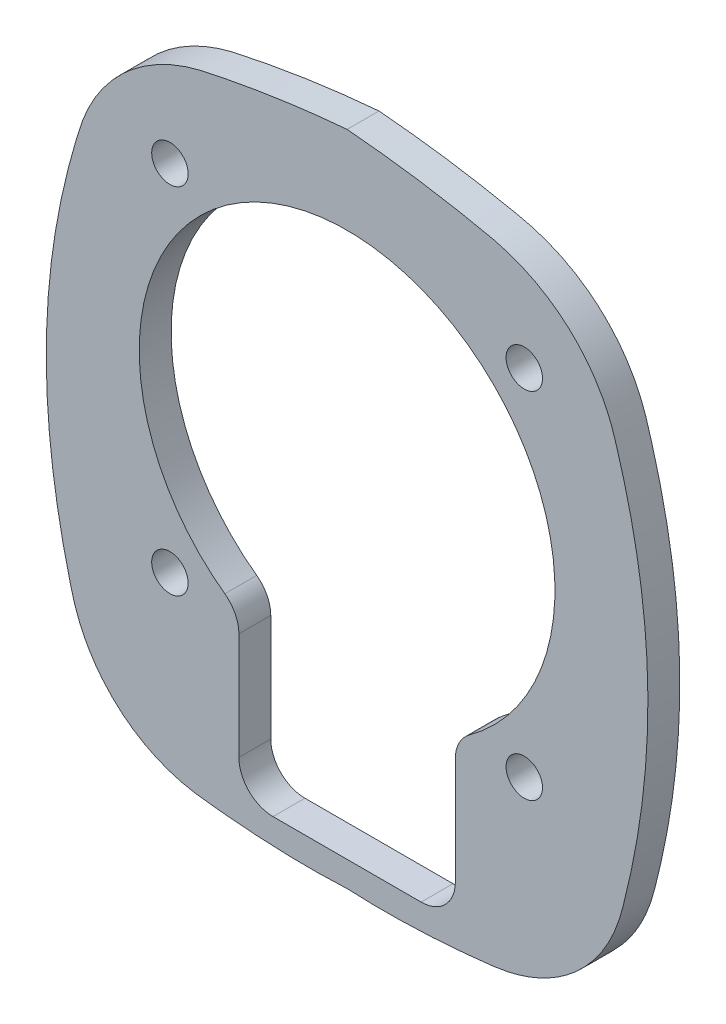
SolidWorks part; units mm, degrees
material "Фанера"
ref_plane "Front Plane" through (0, 0, 0) normal (0, 0, 1) x (1, 0, 0)
ref_plane "Top Plane" through (0, 0, 0) normal (0, 1, 0) x (1, 0, 0)
ref_plane "Right Plane" through (0, 0, 0) normal (1, 0, 0) x (0, 0, -1)
sketch "Эскиз1" plane through (0, 0, 0) normal (0, 0, 1) x (1, 0, 0)
  line L0 (-40.2242, 103.6369) -> (46.2063, 103.6369) construction
  line L1 (0, 130.3745) -> (0, 76.8994) construction
  line L2 (-9.3275, 94.3094) -> (15.3879, 119.0248) construction
  line L3 (0, 85.3869) -> (9.5, 74.0545) construction
  line L4 (-6.5, 74.0545) -> (6.5, 74.0545)
  line L5 (-9.5, 77.0545) -> (-9.5, 86.4523)
  line L7 (9.5, 77.0545) -> (9.5, 86.4523)
  line L8 (-9.5, 74.0545) -> (0, 85.3869) construction
  circle A2 centre (15.5563, 119.1933) radius 1.6
  circle A3 centre (0, 103.6369) radius 5.3081 construction
  circle A4 centre (15.5563, 88.0806) radius 1.6
  circle A5 centre (-15.5563, 88.0806) radius 1.6
  circle A6 centre (-15.5563, 119.1933) radius 1.6
  arc A7 (10.7353, 88.8784) -> (-10.7353, 88.8784) centre (0, 103.6369) ccw
  arc A8 (9.5, 86.4523) -> (10.7353, 88.8784) centre (12.5, 86.4523) cw
  arc A9 (-9.5, 86.4523) -> (-10.7353, 88.8784) centre (-12.5, 86.4523) ccw
  arc A10 (6.5, 74.0545) -> (9.5, 77.0545) centre (6.5, 77.0545) ccw
  arc A11 (-6.5, 74.0545) -> (-9.5, 77.0545) centre (-6.5, 77.0545) cw
  spline S2 degree 3 poles (0, 71.8315) (0.2244, 71.8205) (0.6841, 71.7981) (1.3906, 71.7739) (2.1299, 71.7565) (3.1203, 71.7448) (4.3408, 71.7502) (6.2668, 71.7976) (8.2168, 71.9045) (10.1384, 72.0606) (11.3175, 72.1756) (12.1908, 72.2722) (12.8055, 72.3427) (13.3777, 72.421) (13.9058, 72.5162) (14.7105, 72.6907) (15.8008, 73.0104) (17.1419, 73.5688) (18.4173, 74.2756) (19.9923, 75.3961) (21.3613, 76.7726) (22.4812, 78.3513) (23.0689, 79.4057) (23.4749, 80.2949) (23.7299, 80.9415) (23.9658, 81.6338) (24.1533, 82.3069) (24.3304, 83.0036) (24.4986, 83.6829) (24.6729, 84.4203) (24.8945, 85.4038) (25.1479, 86.6174) (25.5149, 88.5753) (25.8823, 90.9622) (26.3008, 94.8042) (26.4639, 98.6624) (26.342, 102.5416) (26.1061, 105.4752) (25.7399, 108.3214) (25.2271, 111.2025) (24.5892, 114.0183) (24.0127, 116.1281) (23.5945, 117.5099) (23.393, 118.1622) (23.1446, 118.8493) (22.5789, 120.197) (21.3958, 122.2037) (19.3962, 124.3599) (17.5808, 125.6554) (16.3202, 126.3458) (15.5998, 126.6908) (14.887, 126.9875) (14.1857, 127.2392) (13.4993, 127.4491) (12.8305, 127.6212) (12.1801, 127.7583) (11.2759, 127.9477) (10.1086, 128.1784) (8.6711, 128.4415) (7.236, 128.6816) (5.7947, 128.9003) (4.3525, 129.0967) (2.9098, 129.2708) (1.4615, 129.4257) (0.4914, 129.5118) (0, 129.5554) knots 0 0 0 0 0.007245 0.014841 0.02279 0.031091 0.046775 0.062143 0.093208 0.109725 0.124306 0.131407 0.138054 0.144258 0.150025 0.155351 0.170805 0.186581 0.2021 0.217718 0.248803 0.264075 0.280043 0.287632 0.295585 0.302443 0.311207 0.318104 0.325624 0.333769 0.342538 0.358129 0.373741 0.406766 0.435965 0.498333 0.531062 0.561065 0.593194 0.623552 0.655389 0.686255 0.694049 0.701943 0.708265 0.717598 0.749054 0.782774 0.811662 0.820523 0.829105 0.837402 0.845408 0.85312 0.860537 0.867667 0.874549 0.890325 0.906032 0.92167 0.937239 0.953036 0.968597 0.984095 1 1 1 1
  spline S3 degree 3 poles (0, 129.5554) (-0.3274, 129.5268) (-0.9768, 129.4701) (-1.9414, 129.3741) (-3.0563, 129.2533) (-4.3335, 129.0991) (-5.9304, 128.8821) (-7.6867, 128.6115) (-9.5968, 128.2774) (-11.1065, 127.983) (-12.2257, 127.749) (-12.9657, 127.5909) (-13.7283, 127.3844) (-14.5123, 127.1287) (-15.3133, 126.8172) (-16.1261, 126.4457) (-17.4441, 125.7433) (-19.2803, 124.4583) (-20.8975, 122.7541) (-22.0344, 121.1141) (-22.6475, 120.0027) (-23.0613, 119.0569) (-23.2906, 118.4513) (-23.4514, 117.9742) (-23.5936, 117.5109) (-23.9627, 116.299) (-24.5204, 114.2893) (-25.1661, 111.4983) (-25.6891, 108.6448) (-26.202, 104.8285) (-26.4995, 99.9805) (-26.3292, 95.2328) (-25.9381, 91.395) (-25.5882, 89.016) (-25.2309, 87.0441) (-24.9441, 85.6271) (-24.6298, 84.2176) (-24.3543, 83.096) (-24.1482, 82.29) (-24.0189, 81.8236) (-23.8541, 81.2982) (-23.6443, 80.7117) (-23.262, 79.7982) (-22.7055, 78.7194) (-21.6227, 77.0848) (-20.2754, 75.645) (-18.7079, 74.4633) (-17.4335, 73.7134) (-16.0912, 73.1162) (-14.7298, 72.6834) (-13.29, 72.3869) (-12.0158, 72.2517) (-10.861, 72.1299) (-9.8822, 72.0402) (-8.6902, 71.9441) (-7.3519, 71.8569) (-5.8859, 71.7894) (-4.4312, 71.7513) (-2.9337, 71.7436) (-1.4525, 71.766) (-0.4689, 71.8103) (0, 71.8315) knots 0 0 0 0 0.010598 0.021016 0.031255 0.046759 0.062493 0.083214 0.104054 0.125012 0.132806 0.140921 0.149406 0.158267 0.167501 0.177102 0.187061 0.215635 0.248952 0.262143 0.279925 0.289768 0.295408 0.3008 0.305999 0.311032 0.341649 0.373226 0.403368 0.435154 0.497342 0.559715 0.588091 0.621706 0.637214 0.652703 0.668319 0.683771 0.689942 0.695141 0.699374 0.707697 0.715212 0.731297 0.746741 0.778348 0.794222 0.80993 0.825917 0.841493 0.855899 0.873235 0.88278 0.893344 0.904924 0.92134 0.936583 0.952242 0.968255 0.984867 1 1 1 1
  spline S6 degree 3 poles (0.0005, 130.3585) (-0.0171, 130.357) (-0.0462, 130.3544) (-1.979, 130.1857) (-4.8876, 129.8641) (-8.7224, 129.2582) (-11.1223, 128.7926) (-13.0359, 128.4094) (-15.0232, 127.8493) (-17.3518, 126.8009) (-19.874, 125.0131) (-21.9837, 122.7455) (-23.3158, 120.5504) (-24.0971, 118.6337) (-24.6645, 116.74) (-25.3246, 114.3845) (-26.1998, 110.5525) (-26.9602, 105.6954) (-27.3032, 99.7997) (-27.1111, 94.8853) (-26.6923, 90.981) (-26.2473, 88.0692) (-25.7783, 85.667) (-25.339, 83.7483) (-24.996, 82.3391) (-24.576, 80.8596) (-23.7922, 78.961) (-22.4474, 76.7543) (-20.2746, 74.5173) (-17.6592, 72.8344) (-15.2321, 71.9467) (-13.2018, 71.569) (-11.2484, 71.3655) (-8.819, 71.135) (-5.8821, 70.9752) (-2.9406, 70.9249) (-0.9807, 70.9865) (-0.0015, 71.0306) knots -0.000757 -0.000757 -0.000757 -0.000757 -0.000189 0.000189 0.061765 0.093026 0.124287 0.139918 0.155548 0.186809 0.21807 0.249331 0.280592 0.296223 0.311853 0.343114 0.374376 0.436898 0.49942 0.561942 0.593203 0.624464 0.655725 0.671356 0.686986 0.702617 0.718247 0.749508 0.780769 0.81203 0.843291 0.858922 0.874552 0.905813 0.937074 0.968336 0.999597 0.999597 0.999597 0.999597 construction
  spline S7 degree 3 poles (-0.0015, 71.0306) (1.9571, 70.9351) (4.9047, 70.92) (8.8167, 71.1355) (11.2546, 71.365) (13.1961, 71.5697) (15.2349, 71.9462) (17.6573, 72.8341) (20.2745, 74.5172) (22.4473, 76.7538) (23.7915, 78.96) (24.5757, 80.8579) (24.9949, 82.336) (25.3393, 83.7482) (25.7774, 85.6645) (26.2473, 88.0682) (26.6919, 90.9795) (27.1112, 94.8837) (27.3031, 99.7988) (26.9607, 105.6913) (26.2004, 110.549) (25.3257, 114.3811) (24.6652, 116.7361) (24.0982, 118.6308) (23.3179, 120.5463) (21.9828, 122.7473) (19.8733, 125.0135) (17.3516, 126.8011) (15.0221, 127.8495) (13.0373, 128.4093) (11.1214, 128.7928) (8.7226, 129.2581) (4.8873, 129.8647) (1.9798, 130.183) (0.0473, 130.3544) (0.0182, 130.357) (0.0005, 130.3585) knots 0.000403 0.000403 0.000403 0.000403 0.062925 0.094187 0.125448 0.141078 0.156709 0.18797 0.219231 0.250492 0.281753 0.297383 0.313014 0.328644 0.344275 0.375536 0.406797 0.438058 0.50058 0.563102 0.625624 0.656886 0.688147 0.703777 0.719408 0.750669 0.78193 0.813191 0.844452 0.860082 0.875713 0.906974 0.938235 0.999811 1.000189 1.000757 1.000757 1.000757 1.000757 construction
  point P21 (0, 85.3869)
  point P26 (0, 0)
  point P31 (-9.5, 88.0545)
  dimension "D2" = 3.2
  dimension "D4" = 36.5
  dimension "D7" = 3
  dimension "D1" = 45
  dimension "D3" = 22
  dimension "D5" = 19
  dimension "D6" = 14
extrude "Бобышка-Вытянуть1" add sketch "Эскиз1" along normal mid plane 2.8
